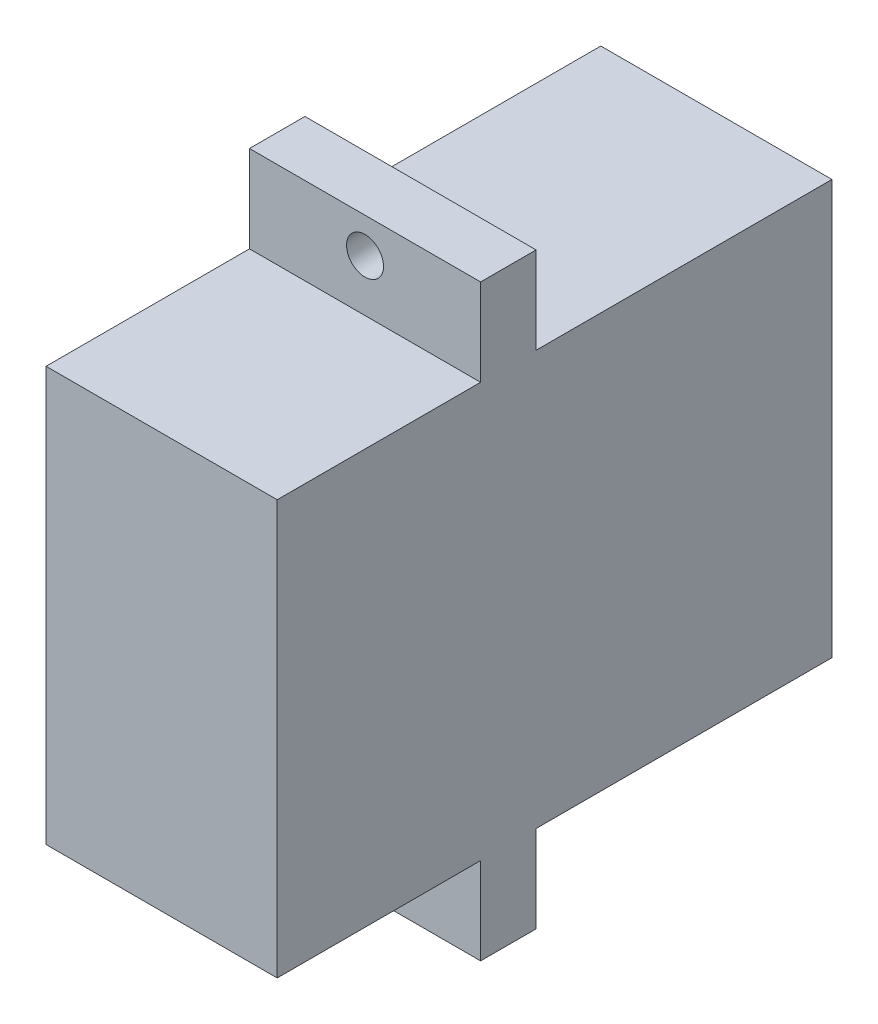
SolidWorks part; units mm, degrees
ref_plane "前视基准面" through (0, 0, 0) normal (0, 0, 1) x (1, 0, 0)
ref_plane "上视基准面" through (0, 0, 0) normal (0, 1, 0) x (1, 0, 0)
ref_plane "右视基准面" through (0, 0, 0) normal (1, 0, 0) x (0, 0, -1)
sketch "草图1" plane through (0, 0, 0) normal (0, 0, 1) x (1, 0, 0)
  line L0 (0, 0) -> (0, -28) construction
  line L1 (0, 0) -> (0, 1.9) construction
  line L2 (-6.25, 1.9) -> (6.25, 1.9)
  line L3 (-6.25, 1.9) -> (-6.25, -29.9)
  line L4 (-6.25, -29.9) -> (6.25, -29.9)
  line L5 (6.25, 1.9) -> (6.25, -29.9)
  line L6 (0, -28) -> (0, -29.9) construction
  line L7 (0, 0) -> (-6.25, 0) construction
  line L8 (0, 0) -> (6.25, 0) construction
  circle A0 centre (0, 0) radius 1
  circle A1 centre (0, -28) radius 1
  dimension "D2" = 12.5
  dimension "D1" = 28
  dimension "D3" = 31.8
extrude "凸台-拉伸1" add sketch "草图1" along normal blind 3 contours L3 L4 L5 L2
sketch "草图2" plane through (0, 0, 3) normal (0, 0, 1) x (1, 0, 0)
  line L0 (-6.25, 1.9) -> (-6.25, -29.9) construction
  line L1 (-6.25, -25.2) -> (6.25, -25.2)
  line L2 (-6.25, -25.2) -> (-6.25, -2.8)
  line L3 (-6.25, -2.8) -> (6.25, -2.8)
  line L4 (6.25, -25.2) -> (6.25, -2.8)
  line L5 (6.25, -29.9) -> (6.25, 1.9) construction
  line L6 (6.25, -2.8) -> (6.25, 1.9)
  line L7 (-6.25, -25.2) -> (-6.25, -29.9) construction
  line L8 (6.25, -2.8) -> (6.25, -25.2)
  line L9 (-6.25, -25.2) -> (-6.25, -2.8)
  line M7 (-6.25, 1.9) -> (-6.25, -29.9)
  line M9 (6.25, -29.9) -> (6.25, 1.9)
  dimension "D1" = 22.4
extrude "凸台-拉伸2" add sketch "草图2" along normal blind 11 contours L3 L1 M7 M9
sketch "草图3" plane through (0, 0, 0) normal (0, 0, -1) x (-1, 0, 0)
  line L0 (6.25, 1.9) -> (6.25, -29.9) construction
  line L1 (6.25, -2.8) -> (-6.25, -2.8)
  line L2 (6.25, -2.8) -> (6.25, -25.2)
  line L3 (6.25, -25.2) -> (-6.25, -25.2)
  line L4 (-6.25, -2.8) -> (-6.25, -25.2)
  line L5 (-6.25, -29.9) -> (-6.25, 1.9) construction
  line L6 (-6.25, 1.9) -> (6.25, 1.9) construction
  line L7 (6.25, -29.9) -> (-6.25, -29.9) construction
  dimension "D1" = 4.7
  dimension "D2" = 4.7
extrude "凸台-拉伸4" add sketch "草图3" along normal blind 16
